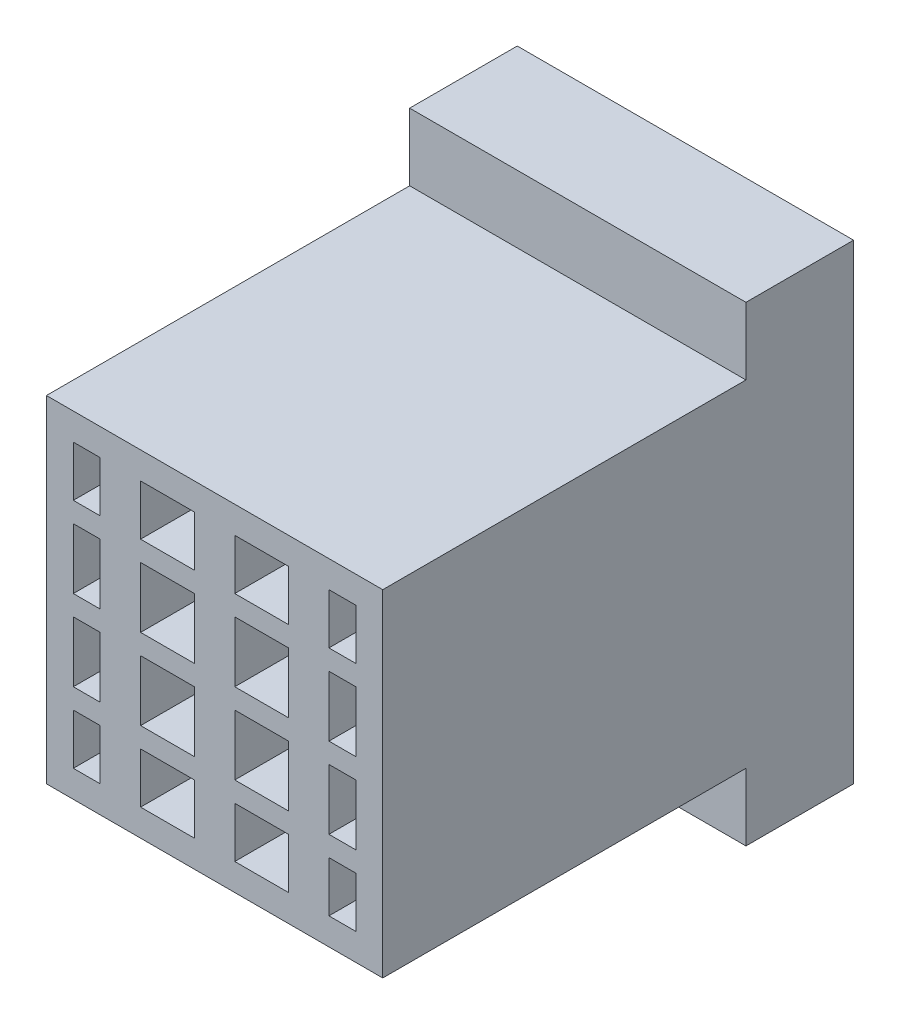
SolidWorks part; units mm, degrees
ref_plane "前视基准面" through (0, 0, 0) normal (0, 0, 1) x (1, 0, 0)
ref_plane "上视基准面" through (0, 0, 0) normal (0, 1, 0) x (1, 0, 0)
ref_plane "右视基准面" through (0, 0, 0) normal (1, 0, 0) x (0, 0, -1)
sketch "草图8" plane through (0, 0, 0) normal (0, 0, 1) x (1, 0, 0)
  line L0 (0, 7.8741) -> (0, -9.2542) construction
  line L1 (-12.5, -12.5) -> (12.5, -12.5)
  line L2 (-12.5, -12.5) -> (-12.5, 12.5)
  line L3 (-12.5, 12.5) -> (12.5, 12.5)
  line L4 (12.5, -12.5) -> (12.5, 12.5)
  line L5 (-12.5, -12.5) -> (12.5, 12.5) construction
  line L6 (-12.5, 12.5) -> (12.5, -12.5) construction
  line L7 (-16.0619, 0) -> (15.5648, 0) construction
  line L8 (-3.5, 7.8741) -> (-3.5, -9.2542) construction
  line L9 (-9.5, 7.8741) -> (-9.5, -9.2542) construction
  line L10 (5.5, 10.5) -> (1.5, 10.5)
  line L15 (-5.5, -10.5) -> (-1.5, -10.5)
  line L20 (-5.5, -10.5) -> (-5.5, 10.5)
  line L21 (-5.5, 10.5) -> (-1.5, 10.5)
  line L26 (-1.5, -10.5) -> (-1.5, 10.5)
  line L27 (-5.5, -10.5) -> (-1.5, 10.5) construction
  line L28 (-5.5, 10.5) -> (-1.5, -10.5) construction
  line L29 (-10.5, -10.5) -> (-8.5, -10.5)
  line L30 (-10.5, -10.5) -> (-10.5, 10.5)
  line L31 (-10.5, 10.5) -> (-8.5, 10.5)
  line L32 (-8.5, -10.5) -> (-8.5, 10.5)
  line L33 (-10.5, -10.5) -> (-8.5, 10.5) construction
  line L34 (-10.5, 10.5) -> (-8.5, -10.5) construction
  line L35 (1.5, -10.5) -> (1.5, 10.5)
  line L36 (5.5, -10.5) -> (1.5, -10.5)
  line L37 (5.5, -10.5) -> (5.5, 10.5)
  line L38 (10.5, 10.5) -> (8.5, 10.5)
  line L39 (8.5, -10.5) -> (8.5, 10.5)
  line L40 (10.5, -10.5) -> (8.5, -10.5)
  line L41 (10.5, -10.5) -> (10.5, 10.5)
  point P0 (0, 0)
  point P14 (-7, 0)
  point P15 (-3.5, 0)
  point P17 (-3, 0)
  point P21 (-9.5, 0)
  point P22 (-9, 0)
  dimension "D1" = 3.5
  dimension "D2" = 6
extrude "凸台-拉伸7" add sketch "草图8" along normal blind 25
sketch "草图9" plane through (0, 0, 0) normal (0, 0, -1) x (-1, 0, 0)
  line L1 (-12.5, -12.5) -> (12.5, -12.5)
  line L2 (-12.5, -12.5) -> (-12.5, 12.5)
  line L3 (-12.5, 12.5) -> (12.5, 12.5)
  line L4 (12.5, -12.5) -> (12.5, 12.5)
  line L5 (-12.5, -12.5) -> (12.5, 12.5) construction
  line L6 (-12.5, 12.5) -> (12.5, -12.5) construction
  point P0 (0, 0)
extrude "凸台-拉伸8" add sketch "草图9" along normal blind 2
sketch "草图11" plane through (0, 0, -2) normal (0, 0, -1) x (-1, 0, 0)
  line L5 (-12.5, -17.5) -> (12.5, -17.5)
  line L6 (-12.5, -17.5) -> (-12.5, 17.5)
  line L7 (-12.5, 17.5) -> (12.5, 17.5)
  line L8 (12.5, -17.5) -> (12.5, 17.5)
  line L9 (-12.5, -17.5) -> (12.5, 17.5) construction
  line L10 (-12.5, 17.5) -> (12.5, -17.5) construction
  point P0 (0, 0)
extrude "凸台-拉伸9" add sketch "草图11" along normal blind 6
sketch "草图12" plane through (0, 0, -8) normal (0, 0, -1) x (-1, 0, 0)
  line L1 (-10.5, -15) -> (10.5, -15)
  line L2 (-10.5, -15) -> (-10.5, 15)
  line L3 (-10.5, 15) -> (10.5, 15)
  line L4 (10.5, -15) -> (10.5, 15)
  line L5 (-10.5, -15) -> (10.5, 15) construction
  line L6 (-10.5, 15) -> (10.5, -15) construction
  point P0 (0, 0)
extrude "切除-拉伸1" cut sketch "草图12" against normal blind 4
sketch "草图14" plane through (0, 0, 25) normal (0, 0, 1) x (1, 0, 0)
  line L0 (-16.6961, 0) -> (20.7273, 0) construction
  line L1 (-12.5, 12.5) -> (-12.5, -12.5) construction
  line L2 (12.5, -0.75) -> (-12.5, -0.75)
  line L3 (12.5, -0.75) -> (12.5, 0.75)
  line L4 (12.5, 0.75) -> (-12.5, 0.75)
  line L5 (-12.5, -0.75) -> (-12.5, 0.75)
  line L6 (12.5, -0.75) -> (-12.5, 0.75) construction
  line L7 (12.5, 0.75) -> (-12.5, -0.75) construction
  line L12 (12.5, 5.25) -> (-12.5, 5.25)
  line L13 (12.5, 5.25) -> (12.5, 6.75)
  line L14 (12.5, 6.75) -> (-12.5, 6.75)
  line L15 (-12.5, 5.25) -> (-12.5, 6.75)
  line L16 (12.5, 5.25) -> (-12.5, 6.75) construction
  line L17 (12.5, 6.75) -> (-12.5, 5.25) construction
  line L18 (12.5, -6.75) -> (-12.5, -5.25) construction
  line L19 (12.5, -5.25) -> (-12.5, -6.75) construction
  line L20 (-12.5, -5.25) -> (-12.5, -6.75)
  line L21 (12.5, -6.75) -> (-12.5, -6.75)
  line L22 (12.5, -5.25) -> (12.5, -6.75)
  line L23 (12.5, -5.25) -> (-12.5, -5.25)
  point P3 (0, 0)
  point P11 (0, 6)
  point P19 (0, -6)
  dimension "D1" = 2
extrude "凸台-拉伸11" add sketch "草图14" against normal blind 25
sketch "草图15" plane through (0, 0, -8) normal (0, 0, -1) x (-1, 0, 0)
  line L1 (-12.5, -17.5) -> (12.5, -17.5)
  line L2 (-12.5, -17.5) -> (-12.5, 17.5)
  line L3 (-12.5, 17.5) -> (12.5, 17.5)
  line L4 (12.5, -17.5) -> (12.5, 17.5)
  line L5 (-12.5, -17.5) -> (12.5, 17.5) construction
  line L6 (-12.5, 17.5) -> (12.5, -17.5) construction
  point P0 (0, 0)
extrude "凸台-拉伸12" add sketch "草图15" along normal blind 2
sketch "草图16" plane through (0, -12.5, 0) normal (0, -1, 0) x (1, 0, 0)
  line L0 (-7.015, 25) -> (-7.015, -2)
  line L1 (-12.5, 25) -> (12.5, 25) construction
  line L2 (12.5, -2) -> (-12.5, -2) construction
  line L3 (-12.5, 20) -> (12.5, 20)
  line L4 (-12.5, 25) -> (-12.5, -2) construction
  line L5 (12.5, 25) -> (12.5, -2) construction
  dimension "D1" = 5
sketch "草图17" plane through (0, 12.5, 0) normal (0, 1, 0) x (1, 0, 0)
  line L0 (-12.5, -20) -> (12.5, -20)
  line L1 (-7.015, 2) -> (-7.015, -25)
